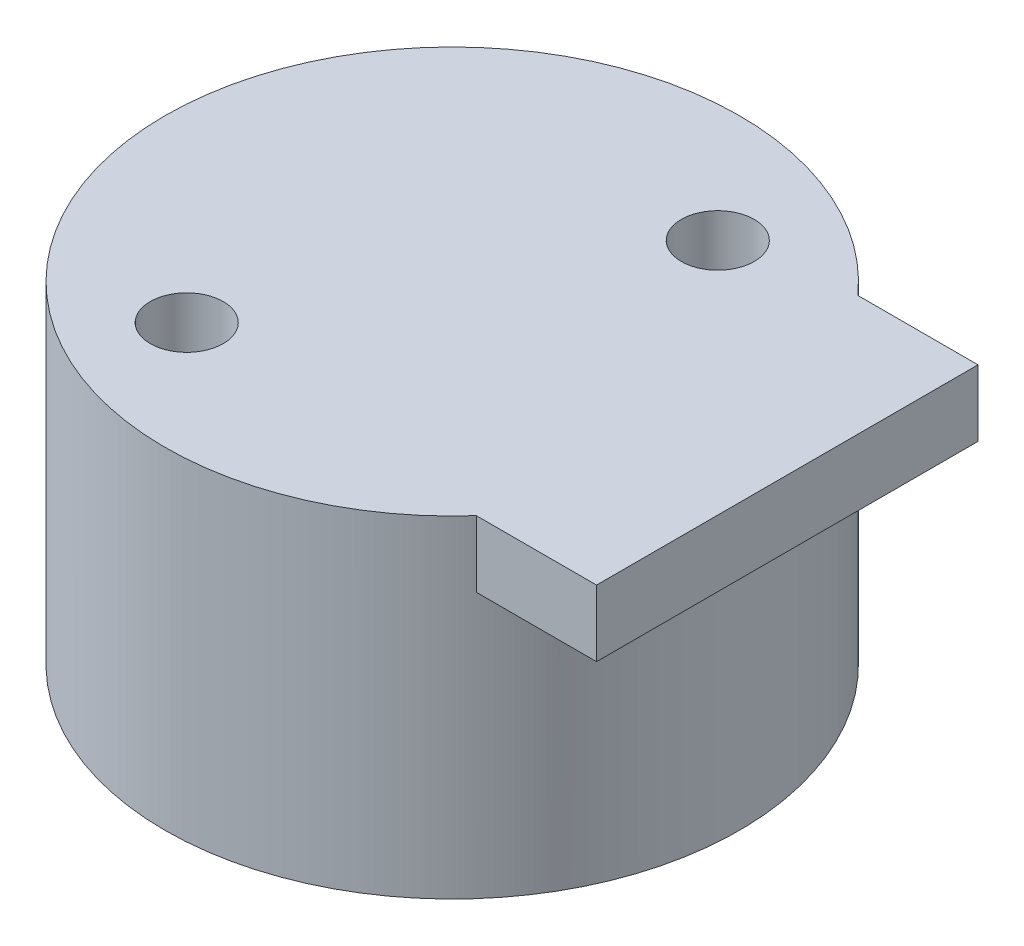
SolidWorks part; units mm, degrees
ref_plane "Front Plane" through (0, 0, 0) normal (0, 0, 1) x (1, 0, 0)
ref_plane "Top Plane" through (0, 0, 0) normal (0, 1, 0) x (1, 0, 0)
ref_plane "Right Plane" through (0, 0, 0) normal (1, 0, 0) x (0, 0, -1)
sketch "Sketch1" plane through (0, 0, 0) normal (0, 1, 0) x (1, 0, 0)
  line L0 (-3.7211, -6.4451) -> (3.7211, 6.4451) construction
  line L1 (0, 0) -> (34.0546, 0) construction
  circle A0 centre (0, 0) radius 10.9982
  circle A1 centre (0, 0) radius 7.4422
  circle A2 centre (3.7211, 6.4451) radius 1.397
  circle A3 centre (-3.7211, -6.4451) radius 1.397
  dimension "D1" = 21.9964
  dimension "D2" = 14.8844
  dimension "D4" = 2.794
  dimension "D5" = 2.794
  dimension "D3" = 60
extrude "Boss-Extrude1" add sketch "Sketch1" along normal blind 12.7 contours A3 A1 A2 | A0 A3 A1 A2
sketch "Sketch2" plane through (0, 12.7, 0) normal (0, 1, 0) x (1, 0, 0)
  line L0 (12.827, 0) -> (0, 0) construction
  line L1 (8.224, 7.3025) -> (12.827, 7.3025)
  line L2 (8.224, 7.3025) -> (8.224, -7.3025)
  line L3 (8.224, -7.3025) -> (12.827, -7.3025)
  line L4 (12.827, 7.3025) -> (12.827, -7.3025)
  circle A0 centre (0, 0) radius 10.9982 construction
  dimension "D1" = 12.827
  dimension "D2" = 14.605
extrude "Boss-Extrude2" add sketch "Sketch2" against normal blind 2.54
equation "\"D5@Sketch1\"=\"D4@Sketch1\""
